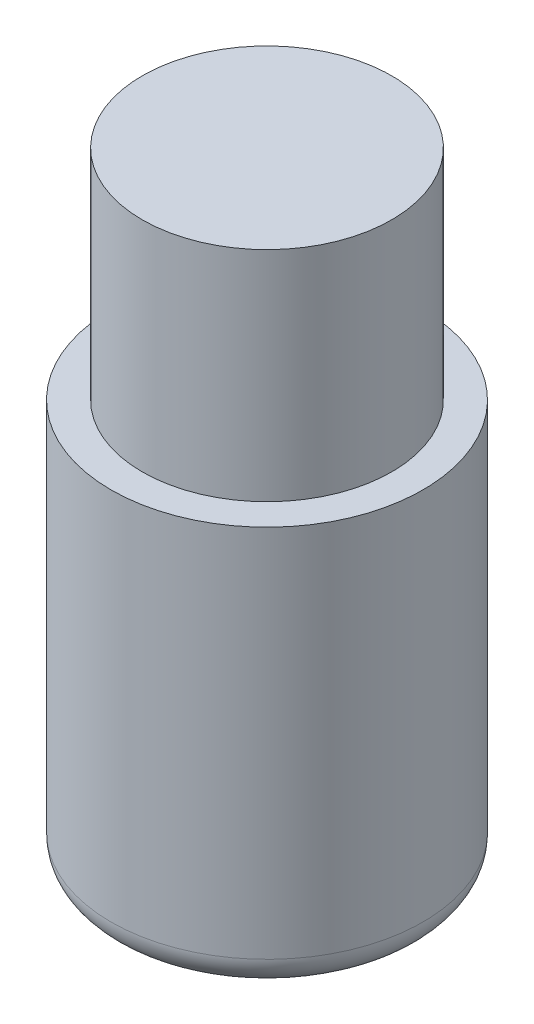
SolidWorks part; units mm, degrees
ref_plane "Front Plane" through (0, 0, 0) normal (0, 0, 1) x (1, 0, 0)
ref_plane "Top Plane" through (0, 0, 0) normal (0, 1, 0) x (1, 0, 0)
ref_plane "Right Plane" through (0, 0, 0) normal (1, 0, 0) x (0, 0, -1)
sketch "Sketch1" plane through (0, 0, 0) normal (0, 1, 0) x (1, 0, 0)
  circle A0 centre (0, 0) radius 5
  dimension "D1" = 10
extrude "Boss-Extrude1" add sketch "Sketch1" along normal blind 13
fillet "Fillet2" radius 1 1 edges at (0, 0, 5)
sketch "Sketch2" plane through (0, 13, 0) normal (0, 1, 0) x (1, 0, 0)
  circle A0 centre (0, 0) radius 4
  dimension "D1" = 8
extrude "Boss-Extrude2" add sketch "Sketch2" along normal blind 7
